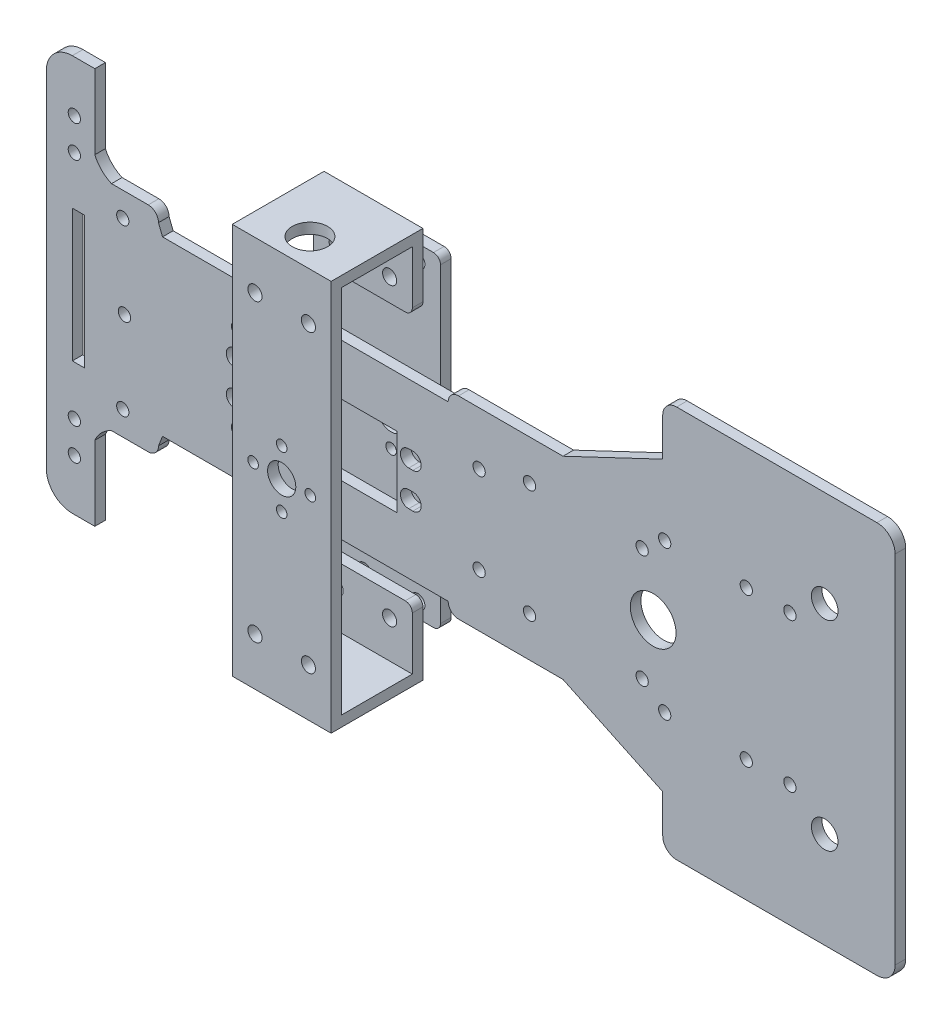
SolidWorks part; units mm, degrees
ref_plane "Alzado" through (0, 0, 0) normal (0, 0, 1) x (1, 0, 0)
ref_plane "Planta" through (0, 0, 0) normal (0, 1, 0) x (1, 0, 0)
ref_plane "Vista lateral" through (0, 0, 0) normal (1, 0, 0) x (0, 0, -1)
sketch "Croquis1" plane through (0, 0, 0) normal (0, 0, 1) x (1, 0, 0)
  line L0 (185.3697, 286.3487) -> (508.7031, 286.3487) construction
sketch "Croquis2" plane through (0, 0, 0) normal (0, 0, 1) x (1, 0, 0)
  line L0 (128.2681, 148.2525) -> (128.2681, 245.7951) construction
  line L1 (128.2681, 245.7951) -> (128.2681, 148.2525) construction
  line L2 (128.2681, 197.0238) -> (368.7103, 197.0238) construction
  line L3 (135.637, 178.2814) -> (135.637, 215.7663)
  line L4 (135.637, 140.8836) -> (142.0162, 140.8836)
  line L5 (142.0162, 140.8836) -> (142.0162, 162.0006)
  line L6 (135.637, 178.2814) -> (139.0474, 178.2814)
  line L7 (146.7416, 166.726) -> (157.15, 166.726)
  line L8 (160.0499, 169.6448) -> (161.2003, 172.5635)
  line L9 (161.2003, 172.5635) -> (242.1071, 172.5635)
  line L10 (139.0474, 178.2814) -> (139.0474, 215.7663)
  line L11 (245.0259, 169.6448) -> (274.6367, 169.6448)
  line L12 (274.6367, 169.6448) -> (302.883, 156.2457)
  line L13 (302.883, 156.2457) -> (302.883, 145.4154)
  line L14 (306.8162, 252.5654) -> (363.5553, 252.5654)
  line L15 (306.8162, 141.4822) -> (363.5553, 141.4822)
  line L16 (302.883, 237.8019) -> (302.883, 248.6323)
  line L17 (368.7103, 146.6021) -> (368.7103, 247.4455)
  line L18 (128.2681, 148.2525) -> (128.2681, 245.7951)
  line L19 (274.6367, 224.4029) -> (302.883, 237.8019)
  line L20 (245.0259, 224.4029) -> (274.6367, 224.4029)
  line L21 (161.2003, 221.4841) -> (242.1071, 221.4841)
  line L22 (160.0499, 224.4028) -> (161.2003, 221.4841)
  line L23 (146.7416, 227.3216) -> (157.15, 227.3216)
  line L24 (135.637, 215.7663) -> (139.0474, 215.7663)
  line L25 (142.0162, 253.164) -> (142.0162, 232.0471)
  line L26 (135.637, 253.164) -> (142.0162, 253.164)
  line L27 (180.0576, 128.7719) -> (245.0259, 128.7719) construction
  line L28 (180.0576, 197.0238) -> (180.0576, 187.0238) construction
  line L29 (180.0576, 197.0238) -> (180.0576, 207.0238) construction
  line L30 (186.1083, 187.0238) -> (186.1083, 207.0238)
  line L31 (186.1083, 207.0238) -> (227.1083, 207.0238)
  line L32 (227.1083, 207.0238) -> (227.6083, 207.0238)
  line L33 (227.6083, 207.0238) -> (227.6083, 187.0238)
  line L34 (227.6083, 187.0238) -> (186.1083, 187.0238)
  line L35 (186.1083, 197.0238) -> (186.1083, 207.0238) construction
  line L36 (186.1083, 202.0238) -> (181.6083, 202.0238) construction
  line L37 (186.1083, 197.0238) -> (186.1083, 187.0238) construction
  line L38 (186.1083, 192.0238) -> (181.6083, 192.0238) construction
  line L39 (186.1083, 197.0238) -> (227.6083, 197.0238) construction
  line L40 (227.6083, 197.0238) -> (206.8583, 197.0238) construction
  line L41 (206.8583, 197.0238) -> (206.8583, 182.7093) construction
  line L42 (181.6083, 202.0238) -> (229.6083, 202.0238) construction
  line L43 (181.6083, 202.0238) -> (182.7876, 202.0238) construction
  line L44 (181.6083, 204.3787) -> (182.7876, 204.3787)
  line L45 (181.6083, 199.6689) -> (182.7876, 199.6689)
  line L46 (181.6083, 192.0238) -> (182.7876, 192.0238) construction
  line L47 (181.6083, 189.6689) -> (182.7876, 189.6689)
  line L48 (181.6083, 194.3787) -> (182.7876, 194.3787)
  line L49 (232.1083, 192.0238) -> (230.9291, 192.0238) construction
  line L50 (232.1083, 189.6689) -> (230.9291, 189.6689)
  line L51 (232.1083, 194.3787) -> (230.9291, 194.3787)
  line L52 (232.1083, 202.0238) -> (230.9291, 202.0238) construction
  line L53 (232.1083, 204.3787) -> (230.9291, 204.3787)
  line L54 (232.1083, 199.6689) -> (230.9291, 199.6689)
  arc A0 (157.15, 166.726) -> (160.0499, 169.6448) centre (157.15, 169.626) ccw
  arc A1 (142.0162, 162.0006) -> (146.7416, 166.726) centre (150.3998, 158.3423) cw
  arc A2 (128.2681, 148.2525) -> (135.637, 140.8836) centre (135.637, 148.2525) ccw
  arc A3 (242.1071, 172.5635) -> (245.0259, 169.6448) centre (245.0259, 172.5635) ccw
  arc A4 (302.883, 145.4154) -> (306.8162, 141.4822) centre (306.8162, 145.4154) ccw
  arc A5 (363.5553, 141.4822) -> (368.7103, 146.6021) centre (363.5903, 146.6022) ccw
  circle A6 centre (136.2151, 164.3931) radius 1.737
  circle A7 centre (136.2151, 155.3584) radius 1.737
  circle A8 centre (149.9283, 173.589) radius 1.737
  circle A9 centre (182.4348, 184.6741) radius 1.737
  circle A10 centre (250.8759, 184.6741) radius 1.737
  circle A11 centre (265.1487, 181.032) radius 1.737
  circle A12 centre (297.0518, 181.032) radius 1.737
  circle A13 centre (303.4417, 175.9483) radius 1.737
  circle A14 centre (326.55, 175.9483) radius 1.737
  circle A15 centre (338.9015, 175.9483) radius 1.737
  circle A16 centre (338.9015, 218.0994) radius 1.737
  circle A17 centre (326.55, 218.0994) radius 1.737
  circle A18 centre (303.4417, 218.0994) radius 1.737
  circle A19 centre (297.0518, 213.0156) radius 1.737
  circle A20 centre (265.1487, 213.0156) radius 1.737
  circle A21 centre (250.8759, 209.3735) radius 1.737
  circle A22 centre (182.4348, 209.3735) radius 1.737
  circle A23 centre (149.9283, 220.4586) radius 1.737
  circle A24 centre (136.2151, 238.6892) radius 1.737
  circle A25 centre (136.2151, 229.6546) radius 1.737
  arc A26 (363.5553, 252.5654) -> (368.7103, 247.4455) centre (363.5903, 247.4455) cw
  arc A27 (302.883, 248.6323) -> (306.8162, 252.5654) centre (306.8162, 248.6323) cw
  arc A28 (242.1071, 221.4841) -> (245.0259, 224.4029) centre (245.0259, 221.4841) cw
  arc A29 (128.2681, 245.7951) -> (135.637, 253.164) centre (135.637, 245.7951) cw
  arc A30 (142.0162, 232.0471) -> (146.7416, 227.3216) centre (150.3998, 235.7053) ccw
  arc A31 (157.15, 227.3216) -> (160.0499, 224.4028) centre (157.15, 224.4217) cw
  circle A32 centre (300.1754, 197.0238) radius 6.4747
  circle A33 centre (150.3998, 197.0238) radius 1.75
  arc A37 (181.6083, 204.3787) -> (181.6083, 199.6689) centre (181.6083, 202.0238) ccw
  arc A38 (182.7876, 199.6689) -> (182.7876, 204.3787) centre (182.7876, 202.0238) ccw
  arc A39 (181.6083, 189.6689) -> (181.6083, 194.3787) centre (181.6083, 192.0238) cw
  arc A40 (182.7876, 194.3787) -> (182.7876, 189.6689) centre (182.7876, 192.0238) cw
  arc A41 (232.1083, 189.6689) -> (232.1083, 194.3787) centre (232.1083, 192.0238) ccw
  arc A42 (230.9291, 194.3787) -> (230.9291, 189.6689) centre (230.9291, 192.0238) ccw
  arc A43 (232.1083, 204.3787) -> (232.1083, 199.6689) centre (232.1083, 202.0238) cw
  arc A44 (230.9291, 199.6689) -> (230.9291, 204.3787) centre (230.9291, 202.0238) cw
  circle A45 centre (348.7625, 168.7389) radius 3.7666
  circle A46 centre (348.7625, 225.3088) radius 3.7666
  point P89 (139.0474, 197.0238)
  point P92 (135.637, 197.0238)
  point P112 (182.1979, 202.0238)
  point P124 (182.1979, 192.0238)
  point P130 (231.5187, 192.0238)
  point P137 (231.5187, 202.0238)
extrude "Saliente-Extruir1" add sketch "Croquis2" along normal blind 3
sketch "Croquis3" plane through (0, 0, 0) normal (0, 0, 1) x (1, 0, 0)
  line L0 (128.2681, 148.2525) -> (128.2681, 245.7951) construction
  line L1 (128.2681, 245.7951) -> (128.2681, 148.2525) construction
  line L2 (128.2681, 197.0238) -> (368.7103, 197.0238) construction
  line L3 (135.637, 178.2814) -> (135.637, 215.7663)
  line L4 (135.637, 140.8836) -> (142.0162, 140.8836)
  line L5 (142.0162, 140.8836) -> (142.0162, 162.0006)
  line L6 (135.637, 178.2814) -> (139.0474, 178.2814)
  line L7 (146.7416, 166.726) -> (157.15, 166.726)
  line L8 (160.0499, 169.6448) -> (161.2003, 172.5635)
  line L9 (161.2003, 172.5635) -> (242.1071, 172.5635)
  line L10 (139.0474, 178.2814) -> (139.0474, 215.7663)
  line L11 (245.0259, 169.6448) -> (274.6367, 169.6448)
  line L12 (274.6367, 169.6448) -> (302.883, 156.2457)
  line L13 (302.883, 156.2457) -> (302.883, 145.4154)
  line L14 (306.8162, 252.5654) -> (363.5553, 252.5654)
  line L15 (306.8162, 141.4822) -> (363.5553, 141.4822)
  line L16 (302.883, 237.8019) -> (302.883, 248.6323)
  line L17 (368.7103, 146.6021) -> (368.7103, 247.4455)
  line L18 (128.2681, 148.2525) -> (128.2681, 245.7951)
  line L19 (274.6367, 224.4029) -> (302.883, 237.8019)
  line L20 (245.0259, 224.4029) -> (274.6367, 224.4029)
  line L21 (161.2003, 221.4841) -> (242.1071, 221.4841)
  line L22 (160.0499, 224.4028) -> (161.2003, 221.4841)
  line L23 (146.7416, 227.3216) -> (157.15, 227.3216)
  line L24 (135.637, 215.7663) -> (139.0474, 215.7663)
  line L25 (142.0162, 253.164) -> (142.0162, 232.0471)
  line L26 (135.637, 253.164) -> (142.0162, 253.164)
  line L27 (180.0576, 128.7719) -> (245.0259, 128.7719) construction
  line L28 (180.0576, 197.0238) -> (180.0576, 187.0238) construction
  line L29 (180.0576, 197.0238) -> (180.0576, 207.0238) construction
  line L30 (186.1083, 187.0238) -> (186.1083, 207.0238)
  line L31 (186.1083, 207.0238) -> (227.1083, 207.0238)
  line L32 (227.1083, 207.0238) -> (227.6083, 207.0238)
  line L33 (227.6083, 207.0238) -> (227.6083, 187.0238)
  line L34 (227.6083, 187.0238) -> (186.1083, 187.0238)
  line L35 (186.1083, 197.0238) -> (186.1083, 207.0238) construction
  line L36 (186.1083, 202.0238) -> (181.6083, 202.0238) construction
  line L37 (186.1083, 197.0238) -> (186.1083, 187.0238) construction
  line L38 (186.1083, 192.0238) -> (181.6083, 192.0238) construction
  line L39 (186.1083, 197.0238) -> (227.6083, 197.0238) construction
  line L40 (227.6083, 197.0238) -> (206.8583, 197.0238) construction
  line L41 (206.8583, 197.0238) -> (206.8583, 182.7093) construction
  line L42 (181.6083, 202.0238) -> (229.6083, 202.0238) construction
  line L43 (181.6083, 202.0238) -> (182.7876, 202.0238) construction
  line L44 (181.6083, 204.3787) -> (182.7876, 204.3787)
  line L45 (181.6083, 199.6689) -> (182.7876, 199.6689)
  line L46 (181.6083, 192.0238) -> (182.7876, 192.0238) construction
  line L47 (181.6083, 189.6689) -> (182.7876, 189.6689)
  line L48 (181.6083, 194.3787) -> (182.7876, 194.3787)
  line L49 (232.1083, 192.0238) -> (230.9291, 192.0238) construction
  line L50 (232.1083, 189.6689) -> (230.9291, 189.6689)
  line L51 (232.1083, 194.3787) -> (230.9291, 194.3787)
  line L52 (232.1083, 202.0238) -> (230.9291, 202.0238) construction
  line L53 (232.1083, 204.3787) -> (230.9291, 204.3787)
  line L54 (232.1083, 199.6689) -> (230.9291, 199.6689)
  arc A0 (157.15, 166.726) -> (160.0499, 169.6448) centre (157.15, 169.626) ccw
  arc A1 (142.0162, 162.0006) -> (146.7416, 166.726) centre (150.3998, 158.3423) cw
  arc A2 (128.2681, 148.2525) -> (135.637, 140.8836) centre (135.637, 148.2525) ccw
  arc A3 (242.1071, 172.5635) -> (245.0259, 169.6448) centre (245.0259, 172.5635) ccw
  arc A4 (302.883, 145.4154) -> (306.8162, 141.4822) centre (306.8162, 145.4154) ccw
  arc A5 (363.5553, 141.4822) -> (368.7103, 146.6021) centre (363.5903, 146.6022) ccw
  circle A6 centre (136.2151, 164.3931) radius 1.737
  circle A7 centre (136.2151, 155.3584) radius 1.737
  circle A8 centre (149.9283, 173.589) radius 1.737
  circle A9 centre (182.4348, 184.6741) radius 1.737
  circle A10 centre (250.8759, 184.6741) radius 1.737
  circle A11 centre (265.1487, 181.032) radius 1.737
  circle A12 centre (297.0518, 181.032) radius 1.737
  circle A13 centre (303.4417, 175.9483) radius 1.737
  circle A14 centre (326.55, 175.9483) radius 1.737
  circle A15 centre (338.9015, 175.9483) radius 1.737
  circle A16 centre (338.9015, 218.0994) radius 1.737
  circle A17 centre (326.55, 218.0994) radius 1.737
  circle A18 centre (303.4417, 218.0994) radius 1.737
  circle A19 centre (297.0518, 213.0156) radius 1.737
  circle A20 centre (265.1487, 213.0156) radius 1.737
  circle A21 centre (250.8759, 209.3735) radius 1.737
  circle A22 centre (182.4348, 209.3735) radius 1.737
  circle A23 centre (149.9283, 220.4586) radius 1.737
  circle A24 centre (136.2151, 238.6892) radius 1.737
  circle A25 centre (136.2151, 229.6546) radius 1.737
  arc A26 (363.5553, 252.5654) -> (368.7103, 247.4455) centre (363.5903, 247.4455) cw
  arc A27 (302.883, 248.6323) -> (306.8162, 252.5654) centre (306.8162, 248.6323) cw
  arc A28 (242.1071, 221.4841) -> (245.0259, 224.4029) centre (245.0259, 221.4841) cw
  arc A29 (128.2681, 245.7951) -> (135.637, 253.164) centre (135.637, 245.7951) cw
  arc A30 (142.0162, 232.0471) -> (146.7416, 227.3216) centre (150.3998, 235.7053) ccw
  arc A31 (157.15, 227.3216) -> (160.0499, 224.4028) centre (157.15, 224.4217) cw
  circle A32 centre (300.1754, 197.0238) radius 6.4747
  circle A33 centre (150.3998, 197.0238) radius 1.75
  arc A37 (181.6083, 204.3787) -> (181.6083, 199.6689) centre (181.6083, 202.0238) ccw
  arc A38 (182.7876, 199.6689) -> (182.7876, 204.3787) centre (182.7876, 202.0238) ccw
  arc A39 (181.6083, 189.6689) -> (181.6083, 194.3787) centre (181.6083, 192.0238) cw
  arc A40 (182.7876, 194.3787) -> (182.7876, 189.6689) centre (182.7876, 192.0238) cw
  arc A41 (232.1083, 189.6689) -> (232.1083, 194.3787) centre (232.1083, 192.0238) ccw
  arc A42 (230.9291, 194.3787) -> (230.9291, 189.6689) centre (230.9291, 192.0238) ccw
  arc A43 (232.1083, 204.3787) -> (232.1083, 199.6689) centre (232.1083, 202.0238) cw
  arc A44 (230.9291, 199.6689) -> (230.9291, 204.3787) centre (230.9291, 202.0238) cw
  circle A45 centre (348.7625, 168.7389) radius 3.7666
  circle A46 centre (348.7625, 225.3088) radius 3.7666
  point P89 (139.0474, 197.0238)
  point P92 (135.637, 197.0238)
  point P112 (182.1979, 202.0238)
  point P124 (182.1979, 192.0238)
  point P130 (231.5187, 192.0238)
  point P137 (231.5187, 202.0238)
sketch "Croquis4" plane through (0, 0, 0) normal (0, 0, 1) x (1, 0, 0)
  line L0 (198.948, 141.5994) -> (198.948, 252.4483)
  line L2 (198.948, 141.5994) -> (226.948, 141.5994)
  line L3 (226.948, 141.5994) -> (226.948, 252.4483)
  line L4 (128.2681, 197.0238) -> (368.7103, 197.0238) construction
  line L5 (246.8101, 197.0238) -> (267.4887, 197.0238) construction
  line L6 (198.948, 252.4483) -> (226.948, 252.4483)
  line L7 (198.948, 197.0238) -> (226.948, 197.0238) construction
  line L8 (226.948, 197.0238) -> (212.948, 197.0238) construction
  line L9 (212.948, 197.0238) -> (212.948, 141.5994) construction
  circle A0 centre (205.3779, 155.173) radius 2
  circle A1 centre (220.5181, 155.173) radius 2
  circle A2 centre (220.5181, 238.8746) radius 2
  circle A3 centre (205.3779, 238.8746) radius 2
  circle A4 centre (212.948, 197.0238) radius 10.5 construction
  circle A5 centre (212.948, 197.0238) radius 8.1 construction
  circle A6 centre (212.948, 205.1238) radius 1.5
  circle A7 centre (212.948, 188.9238) radius 1.5
  circle A8 centre (204.848, 197.0238) radius 1.5
  circle A9 centre (221.048, 197.0238) radius 1.5
  circle A10 centre (212.948, 197.0238) radius 4
  point P10 (226.948, 197.0238)
  point P11 (198.948, 197.0238)
  dimension "D1" = 21
  dimension "D2" = 16.2
ref_plane "Plano1" through (0, 0, 18) normal (0, 0, 1) x (1, 0, 0)
sketch "Croquis5" plane through (0, 0, 18) normal (0, 0, 1) x (1, 0, 0)
  line L0 (198.948, 141.5994) -> (198.948, 252.4483)
  line L2 (198.948, 141.5994) -> (226.948, 141.5994)
  line L3 (226.948, 141.5994) -> (226.948, 252.4483)
  line L5 (246.8101, 197.0238) -> (267.4887, 197.0238) construction
  line L6 (198.948, 252.4483) -> (226.948, 252.4483)
  line L7 (198.948, 197.0238) -> (226.948, 197.0238) construction
  line L8 (226.948, 197.0238) -> (212.948, 197.0238) construction
  line L9 (212.948, 197.0238) -> (212.948, 141.5994) construction
  circle A0 centre (205.3779, 155.173) radius 2
  circle A1 centre (220.5181, 155.173) radius 2
  circle A2 centre (220.5181, 238.8746) radius 2
  circle A3 centre (205.3779, 238.8746) radius 2
  circle A4 centre (212.948, 197.0238) radius 10.5 construction
  circle A5 centre (212.948, 197.0238) radius 8.1 construction
  circle A6 centre (212.948, 205.1238) radius 1.5
  circle A7 centre (212.948, 188.9238) radius 1.5
  circle A8 centre (204.848, 197.0238) radius 1.5
  circle A9 centre (221.048, 197.0238) radius 1.5
  circle A10 centre (212.948, 197.0238) radius 4
  point P10 (226.948, 197.0238)
  point P11 (198.948, 197.0238)
  dimension "D1" = 21
  dimension "D2" = 16.2
extrude "Saliente-Extruir2" add sketch "Croquis5" along normal blind 3 separate body
ref_plane "Plano2" through (0, 0, -10) normal (0, 0, -1) x (-1, 0, 0)
sketch "Croquis8" plane through (0, 0, 18) normal (0, 0, -1) x (-1, 0, 0)
  line L0 (-198.948, 141.5994) -> (-198.948, 144.5994)
  line L1 (-198.948, 141.5994) -> (-198.948, 252.4483) construction
  line L2 (-198.948, 144.5994) -> (-226.948, 144.5994)
  line L3 (-226.948, 141.5994) -> (-226.948, 252.4483) construction
  line L4 (-226.948, 144.5994) -> (-226.948, 141.5994)
  line L5 (-226.948, 141.5994) -> (-198.948, 141.5994)
  line L6 (-198.948, 252.4483) -> (-198.948, 249.4483)
  line L7 (-198.948, 249.4483) -> (-226.948, 249.4483)
  line L8 (-226.948, 249.4483) -> (-226.948, 252.4483)
  line L9 (-226.948, 252.4483) -> (-198.948, 252.4483)
extrude "Saliente-Extruir3" add sketch "Croquis8" along normal blind 20
sketch "Croquis9" plane through (0, 0, -2) normal (0, 0, -1) x (-1, 0, 0)
  line L0 (-198.948, 141.5994) -> (-198.948, 161.5994)
  line L1 (-198.948, 141.5994) -> (-198.948, 252.4483) construction
  line L2 (-198.948, 161.5994) -> (-226.948, 161.5994)
  line L3 (-226.948, 141.5994) -> (-226.948, 252.4483) construction
  line L4 (-226.948, 161.5994) -> (-226.948, 141.5994)
  line L5 (-226.948, 141.5994) -> (-198.948, 141.5994)
  line L6 (-198.948, 252.4483) -> (-198.948, 232.4483)
  line L7 (-198.948, 232.4483) -> (-226.948, 232.4483)
  line L8 (-226.948, 232.4483) -> (-226.948, 252.4483)
  line L9 (-226.948, 252.4483) -> (-198.948, 252.4483)
  circle A0 centre (-205.3779, 155.173) radius 2
  circle A1 centre (-220.5181, 155.173) radius 2
  circle A2 centre (-205.3779, 238.8746) radius 2
  circle A3 centre (-220.5181, 238.8746) radius 2
extrude "Saliente-Extruir4" add sketch "Croquis9" along normal blind 3
sketch "Croquis11" plane through (0, 0, -10) normal (0, 0, -1) x (-1, 0, 0)
  line L0 (-198.948, 141.5994) -> (-198.948, 252.4483) construction
  line L1 (-226.948, 151.0238) -> (-198.948, 151.0238)
  line L2 (-226.948, 151.0238) -> (-226.948, 243.0238)
  line L3 (-226.948, 243.0238) -> (-198.948, 243.0238)
  line L4 (-198.948, 151.0238) -> (-198.948, 243.0238)
  line L5 (-226.948, 151.0238) -> (-198.948, 243.0238) construction
  line L6 (-226.948, 243.0238) -> (-198.948, 151.0238) construction
  circle A0 centre (-220.5181, 238.8746) radius 2
  circle A1 centre (-205.3779, 238.8746) radius 2
  circle A2 centre (-205.3779, 155.173) radius 2
  circle A3 centre (-220.5181, 155.173) radius 2
  circle A4 centre (-212.948, 197.0238) radius 4
  circle A5 centre (-204.848, 197.0238) radius 1.5
  circle A6 centre (-212.948, 205.1238) radius 1.5
  circle A7 centre (-212.948, 188.9238) radius 1.5
  circle A8 centre (-221.048, 197.0238) radius 1.5
  point P0 (-212.948, 197.0238)
extrude "Saliente-Extruir5" add sketch "Croquis11" along normal blind 3 separate body
fillet "Redondeo1" radius 2 4 edges at (226.948, 243.0238, -11.5) (198.948, 243.0238, -11.5) (226.948, 151.0238, -11.5) (198.948, 151.0238, -11.5)
fillet "Redondeo2" radius 2 4 edges at (198.948, 232.4483, -3.5) (226.948, 232.4483, -3.5) (226.948, 161.5994, -3.5) (198.948, 161.5994, -3.5)
ref_plane "Plano3" through (0, 0, 13) normal (0, 0, 1) x (1, 0, 0)
sketch "Croquis14" plane through (0, 141.5994, 0) normal (0, -1, 0) x (1, 0, 0)
  line L0 (198.948, 21.4177) -> (198.948, 21) construction
  line L1 (198.948, 21) -> (226.948, 21) construction
  line L2 (226.948, 21) -> (212.948, 21) construction
  line L3 (212.948, 21) -> (212.948, 13) construction
  line L4 (61.7542, 13) -> (-61.7542, 13) construction
  circle A0 centre (212.948, 13) radius 5
extrude "Cortar-Extruir1" cut sketch "Croquis14" against normal blind 143
